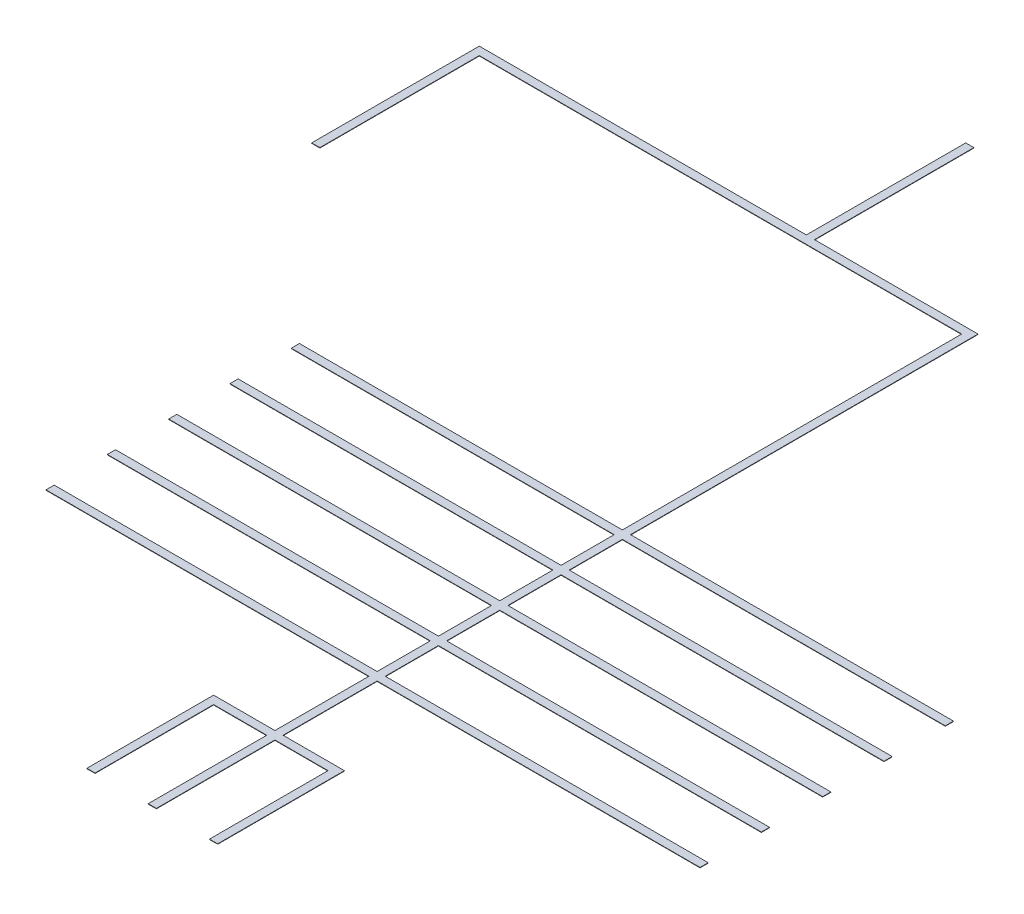
SolidWorks part; units mm, degrees
ref_plane "前视基准面" through (0, 0, 0) normal (0, 0, 1) x (1, 0, 0)
ref_plane "上视基准面" through (0, 0, 0) normal (0, 1, 0) x (1, 0, 0)
ref_plane "右视基准面" through (0, 0, 0) normal (1, 0, 0) x (0, 0, -1)
sketch "草图1" plane through (0, 0, 0) normal (0, 1, 0) x (1, 0, 0)
  line L0 (-2399.3753, 2799.6876) -> (2400.6247, 2799.6876)
  line L1 (-2399.3753, 2799.6876) -> (-2399.3753, -2800.3124)
  line L2 (-2399.3753, -2800.3124) -> (2400.6247, -2800.3124)
  line L3 (2400.6247, 2799.6876) -> (2400.6247, -2800.3124)
  line L4 (0.6247, -2800.3124) -> (0.6247, 2799.6876) construction
  line L6 (-2399.3753, 1999.6876) -> (2400.6247, 1999.6876) construction
  line L7 (-2399.3753, 1199.6876) -> (2400.6247, 1199.6876) construction
  line L8 (-2399.3753, 399.6876) -> (2400.6247, 399.6876) construction
  line L9 (-2399.3753, -400.3124) -> (2400.6247, -400.3124) construction
  line L10 (-2399.3753, -1200.3124) -> (2400.6247, -1200.3124) construction
  line L11 (-2399.3753, -2000.3124) -> (2400.6247, -2000.3124) construction
  line L12 (-1599.3753, 2799.6876) -> (-1599.3753, -2800.3124) construction
  line L13 (-799.3753, 2799.6876) -> (-799.3753, -2800.3124) construction
  line L14 (0.6247, 2799.6876) -> (0.6247, -2800.3124) construction
  line L15 (800.6247, 2799.6876) -> (800.6247, -2800.3124) construction
  line L16 (1600.6247, 2799.6876) -> (1600.6247, -2800.3124) construction
  point P0 (0.6247, -0.3124)
sketch "草图2" plane through (0, 0, 0) normal (0, 1, 0) x (1, 0, 0)
  line L0 (-1199.3753, 399.6876) -> (-1199.3753, 799.6876) construction
  line L1 (-2399.3753, 399.6876) -> (2400.6247, 399.6876) construction
  line L2 (-2399.3753, 1199.6876) -> (2400.6247, 1199.6876) construction
  line L3 (-1199.3753, 799.6876) -> (-9.3753, 799.6876) construction
  line L4 (-1599.3753, 2799.6876) -> (-1599.3753, -2800.3124) construction
  line L5 (0.6247, -2800.3124) -> (0.6247, 2799.6876) construction
  line L9 (-399.3753, 1199.6876) -> (-399.3753, 799.6876) construction
  line L17 (0.6247, 799.6876) -> (0.6247, -1200.3124) construction
  line L18 (-2399.3753, -1200.3124) -> (2400.6247, -1200.3124) construction
  line L96 (-149.3753, -900.3124) -> (150.6247, -900.3124) construction
  line L104 (-149.3753, -900.3124) -> (-149.3753, -1200.3124) construction
  line L106 (150.6247, -900.3124) -> (150.6247, -1200.3124) construction
  line L109 (-799.3753, -650.3124) -> (800.6247, -650.3124) construction
  line L111 (-799.3753, 2799.6876) -> (-799.3753, -2800.3124) construction
  line L113 (800.6247, 2799.6876) -> (800.6247, -2800.3124) construction
  line L116 (-2399.3753, -400.3124) -> (2400.6247, -400.3124) construction
  line L119 (-799.3753, -500.3124) -> (800.6247, -500.3124) construction
  line L122 (-799.3753, -350.3124) -> (800.6247, -350.3124) construction
  line L125 (-799.3753, -200.3124) -> (800.6247, -200.3124) construction
  line L129 (-799.3753, -50.3124) -> (800.6247, -50.3124) construction
  line L130 (-1189.3753, 399.6876) -> (-1189.3753, 789.6876)
  line L132 (-1189.3753, 789.6876) -> (-9.3753, 789.6876)
  line L148 (-1209.3753, 399.6876) -> (-1209.3753, 809.6876)
  line L149 (-1209.3753, 809.6876) -> (-409.3753, 809.6876)
  line L161 (-1189.3753, 399.6876) -> (-1209.3753, 399.6876)
  line L179 (-409.3753, 1199.6876) -> (-409.3753, 809.6876)
  line L180 (-389.3753, 1199.6876) -> (-389.3753, 809.6876)
  line L181 (-409.3753, 1199.6876) -> (-389.3753, 1199.6876)
  line L183 (-389.3753, 809.6876) -> (10.6247, 809.6876)
  line L184 (-1209.3753, 809.6876) -> (10.6247, 809.6876) construction
  line L185 (-389.3753, 1199.6876) -> (-389.3753, 799.6876) construction
  line L186 (-409.3753, 1199.6876) -> (-409.3753, 799.6876) construction
  line L188 (-9.3753, 789.6876) -> (-9.3753, -40.3124)
  line L190 (-9.3753, 789.6876) -> (-9.3753, -1050.3124) construction
  line L192 (10.6247, 809.6876) -> (10.6247, -1050.3124) construction
  line L194 (-799.3753, -60.3124) -> (-9.3753, -60.3124)
  line L196 (-799.3753, -210.3124) -> (-9.3753, -210.3124)
  line L200 (-799.3753, -360.3124) -> (-9.3753, -360.3124)
  line L202 (-799.3753, -510.3124) -> (-9.3753, -510.3124)
  line L205 (-799.3753, -660.3124) -> (-9.3753, -660.3124)
  line L208 (-139.3753, -910.3124) -> (-139.3753, -1200.3124)
  line L211 (-139.3753, -910.3124) -> (-9.3753, -910.3124)
  line L214 (140.6247, -910.3124) -> (140.6247, -1200.3124)
  line L218 (10.6247, 799.6876) -> (10.6247, -40.3124)
  line L221 (-799.3753, -40.3124) -> (-9.3753, -40.3124)
  line L223 (-799.3753, -190.3124) -> (-9.3753, -190.3124)
  line L225 (-799.3753, -340.3124) -> (-9.3753, -340.3124)
  line L226 (-799.3753, -490.3124) -> (-9.3753, -490.3124)
  line L227 (-799.3753, -640.3124) -> (-9.3753, -640.3124)
  line L228 (-159.3753, -890.3124) -> (-159.3753, -1200.3124)
  line L231 (-159.3753, -890.3124) -> (-9.3753, -890.3124)
  line L232 (160.6247, -890.3124) -> (160.6247, -1200.3124)
  line L234 (-9.3753, -1200.3124) -> (10.6247, -1200.3124)
  line L235 (-799.3753, -60.3124) -> (-799.3753, -40.3124)
  line L236 (800.6247, -60.3124) -> (800.6247, -40.3124)
  line L237 (-799.3753, -210.3124) -> (-799.3753, -190.3124)
  line L238 (800.6247, -210.3124) -> (800.6247, -190.3124)
  line L239 (-799.3753, -360.3124) -> (-799.3753, -340.3124)
  line L240 (800.6247, -360.3124) -> (800.6247, -340.3124)
  line L241 (-799.3753, -510.3124) -> (-799.3753, -490.3124)
  line L242 (800.6247, -510.3124) -> (800.6247, -490.3124)
  line L243 (-799.3753, -660.3124) -> (-799.3753, -640.3124)
  line L244 (800.6247, -660.3124) -> (800.6247, -640.3124)
  line L245 (-139.3753, -1200.3124) -> (-159.3753, -1200.3124)
  line L246 (140.6247, -1200.3124) -> (160.6247, -1200.3124)
  line L247 (-1199.3753, 799.6876) -> (0.6247, 799.6876) construction
  line L248 (-9.3753, 799.6876) -> (-9.3753, -1200.3124) construction
  line L249 (10.6247, 809.6876) -> (10.6247, 799.6876)
  line L250 (10.6247, -40.3124) -> (800.6247, -40.3124)
  line L251 (0.6247, 799.6876) -> (0.6247, -1050.3124) construction
  line L252 (-799.3753, -40.3124) -> (800.6247, -40.3124) construction
  line L253 (-9.3753, -60.3124) -> (-9.3753, -190.3124)
  line L254 (10.6247, -60.3124) -> (10.6247, -190.3124)
  line L255 (10.6247, 799.6876) -> (10.6247, -1200.3124) construction
  line L256 (10.6247, -60.3124) -> (800.6247, -60.3124)
  line L257 (-799.3753, -60.3124) -> (800.6247, -60.3124) construction
  line L258 (10.6247, -190.3124) -> (800.6247, -190.3124)
  line L259 (-799.3753, -190.3124) -> (800.6247, -190.3124) construction
  line L260 (-9.3753, -210.3124) -> (-9.3753, -340.3124)
  line L261 (10.6247, -210.3124) -> (800.6247, -210.3124)
  line L262 (-799.3753, -210.3124) -> (800.6247, -210.3124) construction
  line L263 (10.6247, -210.3124) -> (10.6247, -340.3124)
  line L264 (10.6247, -340.3124) -> (800.6247, -340.3124)
  line L265 (-799.3753, -340.3124) -> (800.6247, -340.3124) construction
  line L266 (-9.3753, -360.3124) -> (-9.3753, -490.3124)
  line L267 (10.6247, -360.3124) -> (800.6247, -360.3124)
  line L268 (-799.3753, -360.3124) -> (800.6247, -360.3124) construction
  line L269 (10.6247, -360.3124) -> (10.6247, -490.3124)
  line L270 (10.6247, -490.3124) -> (800.6247, -490.3124)
  line L271 (-799.3753, -490.3124) -> (800.6247, -490.3124) construction
  line L272 (-9.3753, -510.3124) -> (-9.3753, -640.3124)
  line L273 (10.6247, -510.3124) -> (10.6247, -640.3124)
  line L274 (10.6247, -510.3124) -> (800.6247, -510.3124)
  line L275 (-799.3753, -510.3124) -> (800.6247, -510.3124) construction
  line L276 (10.6247, -640.3124) -> (800.6247, -640.3124)
  line L277 (-799.3753, -640.3124) -> (800.6247, -640.3124) construction
  line L278 (-9.3753, -660.3124) -> (-9.3753, -890.3124)
  line L279 (10.6247, -660.3124) -> (800.6247, -660.3124)
  line L280 (-799.3753, -660.3124) -> (800.6247, -660.3124) construction
  line L281 (10.6247, -660.3124) -> (10.6247, -890.3124)
  line L282 (10.6247, -890.3124) -> (160.6247, -890.3124)
  line L283 (-159.3753, -890.3124) -> (160.6247, -890.3124) construction
  line L284 (-9.3753, -910.3124) -> (-9.3753, -1200.3124)
  line L285 (10.6247, -910.3124) -> (140.6247, -910.3124)
  line L286 (-139.3753, -910.3124) -> (140.6247, -910.3124) construction
  line L287 (10.6247, -910.3124) -> (10.6247, -1200.3124)
  dimension "D3" = 300
  dimension "D1" = 400
  dimension "D2" = 400
  dimension "D4" = 150
  dimension "D6" = 250
  dimension "D7" = 5
  dimension "D8" = 150
  dimension "D10" = 10
  dimension "D18" = 10
  dimension "D20" = 400
  dimension "D5" = 150
  dimension "D9" = 10
  dimension "D19" = 10
  dimension "D21" = 10
  dimension "D22" = 10
extrude "凸台-拉伸1" add sketch "草图2" along normal blind 1
